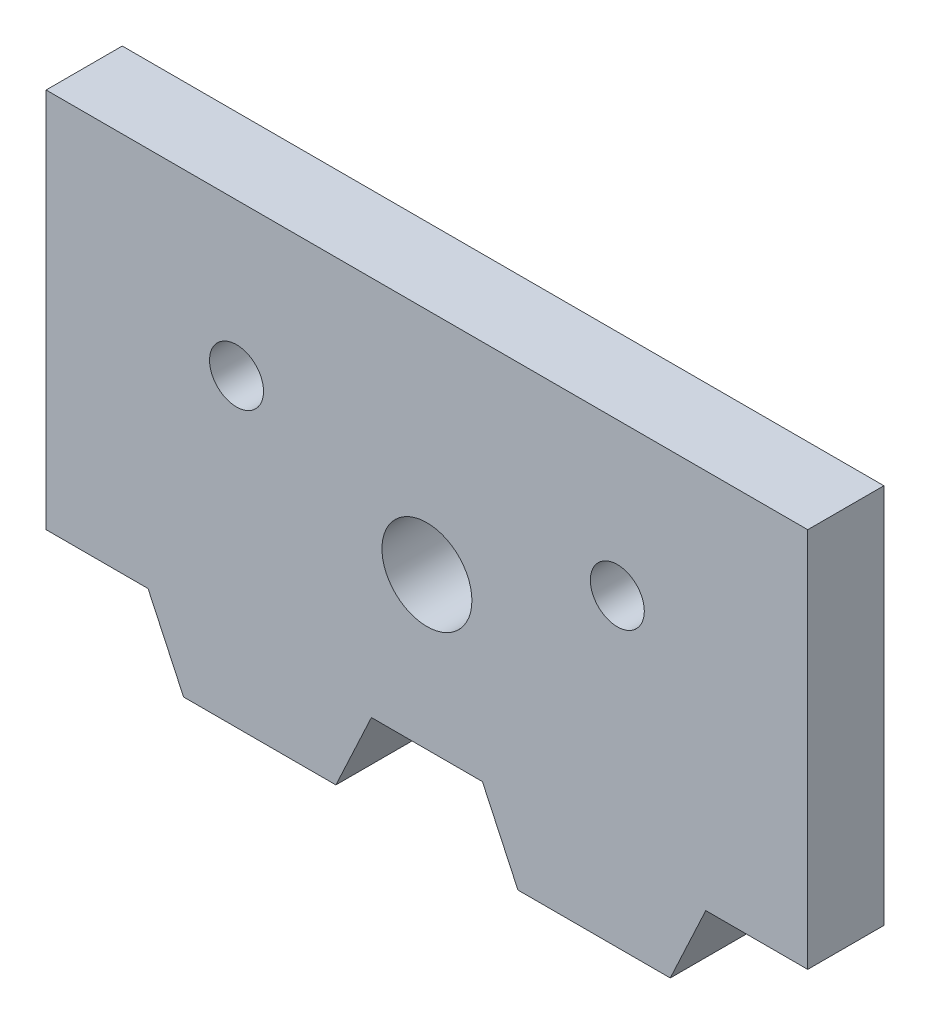
SolidWorks part; units mm, degrees
ref_plane "Front Plane" through (0, 0, 0) normal (0, 0, 1) x (1, 0, 0)
ref_plane "Top Plane" through (0, 0, 0) normal (0, 1, 0) x (1, 0, 0)
ref_plane "Right Plane" through (0, 0, 0) normal (1, 0, 0) x (0, 0, -1)
sketch "Sketch1" plane through (0, 0, 0) normal (0, 0, 1) x (1, 0, 0)
  line L0 (-63.5, -25.2641) -> (-46.5, -25.2641)
  line L1 (15.1779, -37.9641) -> (40.5779, -37.9641)
  line L2 (-63.5, -25.2641) -> (-63.5, 38.2359)
  line L3 (-63.5, 38.2359) -> (63.5, 38.2359)
  line L4 (63.5, -25.2641) -> (63.5, 38.2359)
  line L5 (9.2558, -25.2641) -> (-9.2558, -25.2641)
  line L6 (-46.5, -25.2641) -> (-40.5779, -37.9641)
  line L7 (-9.2558, -25.2641) -> (-15.1779, -37.9641)
  line L8 (0, 0) -> (0, -50.3532) construction
  line L9 (-15.1779, -37.9641) -> (-40.5779, -37.9641)
  line L11 (9.2558, -25.2641) -> (15.1779, -37.9641)
  line L12 (-63.5, -37.9641) -> (63.5, -37.9641) construction
  line L13 (46.5, -25.2641) -> (40.5779, -37.9641)
  line L14 (-63.5, -25.2641) -> (63.5, -25.2641) construction
  line L15 (46.5, -25.2641) -> (63.5, -25.2641)
  line L16 (63.5, 38.2359) -> (63.5, 12.8359)
  circle A1 centre (0, 0) radius 7.5
  circle A2 centre (31.75, 12.8359) radius 4.5
  circle A3 centre (-31.75, 12.8359) radius 4.5
  point P0 (0, 0)
  dimension "D10" = 31.75
  dimension "D2" = 127
  dimension "D3" = 12.7
  dimension "D4" = 17
  dimension "D5" = 17
  dimension "D6" = 115
  dimension "D7" = 115
  dimension "D8" = 25.4
  dimension "D9" = 25.4
  dimension "D11" = 76.2
extrude "Boss-Extrude1" add sketch "Sketch1" along normal blind 12.7 contours L13 L15 L4 L3 L2 L0 L6 L9 L7 L5 L11 L1 A1 A2 A3
